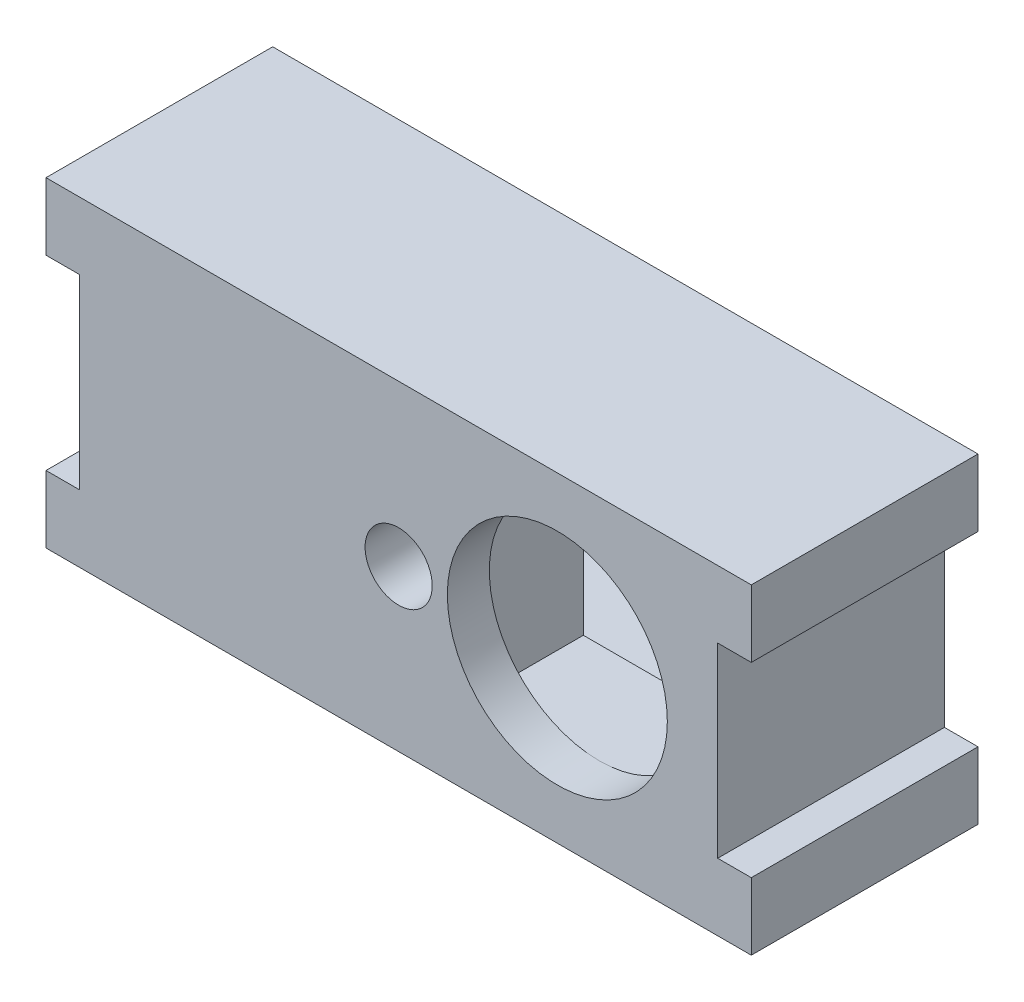
SolidWorks part; units mm, degrees
ref_plane "Front Plane" through (0, 0, 0) normal (0, 0, 1) x (1, 0, 0)
ref_plane "Top Plane" through (0, 0, 0) normal (0, 1, 0) x (1, 0, 0)
ref_plane "Right Plane" through (0, 0, 0) normal (1, 0, 0) x (0, 0, -1)
sketch "Sketch2" plane through (0, 0, 0) normal (0, 0, 1) x (1, 0, 0)
  line L0 (-19, 9.55) -> (-19, -9.55)
  line L1 (-16, 6.55) -> (16, 6.55) construction
  line L2 (-16, 6.55) -> (-16, -6.55) construction
  line L3 (-16, -6.55) -> (16, -6.55) construction
  line L4 (16, 6.55) -> (16, -6.55) construction
  line L5 (-16, 6.55) -> (16, -6.55) construction
  line L6 (-16, -6.55) -> (16, 6.55) construction
  line L7 (-19, -9.55) -> (19, -9.55)
  line L8 (19, 9.55) -> (19, -9.55)
  line L9 (-19, 9.55) -> (19, 9.55)
  circle A0 centre (9.45, 0) radius 6.55
  circle A1 centre (0, 0) radius 2
  point P0 (0, 0)
  point P15 (-16, 0)
  dimension "D5" = 4
  dimension "D1" = 32
  dimension "D2" = 13.1
  dimension "D4" = 16
  dimension "D3" = 3
extrude "Boss-Extrude1" add sketch "Sketch2" against normal blind 2.5
sketch "Sketch3" plane through (0, 0, -2.5) normal (0, 0, -1) x (-1, 0, 0)
  line L0 (-2.5, 6.55) -> (-2.5, -6.55)
  line L1 (19, 9.55) -> (-19, 9.55) construction
  line L2 (19, -9.55) -> (-19, -9.55) construction
  line L3 (-19, -9.55) -> (19, -9.55)
  line L4 (19, -9.55) -> (19, -5.55)
  line L5 (19, -5.55) -> (2.5, -5.55)
  line L6 (2.5, -5.55) -> (2.5, 5.55)
  line L7 (2.5, 5.55) -> (19, 5.55)
  line L9 (19, 9.55) -> (-19, 9.55)
  line L10 (19, 9.55) -> (19, -9.55) construction
  line L11 (16, 6.55) -> (-16, 6.55) construction
  line L12 (-2.5, 6.55) -> (-16, 6.55)
  line L13 (-16, 6.55) -> (-16, -6.55) construction
  line L14 (-16, 6.55) -> (-16, -6.55)
  line L16 (19, 9.55) -> (19, 5.55)
  line L17 (-2.5, -6.55) -> (-16, -6.55)
  line L18 (-19, 9.55) -> (-19, -9.55)
  line L19 (16, -6.55) -> (-16, -6.55) construction
  circle A0 centre (0, 0) radius 2 construction
  circle A1 centre (0, 0) radius 2
  dimension "D1" = 1
  dimension "D2" = 1
  dimension "D3" = 2.5
  dimension "D4" = 5
extrude "Boss-Extrude2" add sketch "Sketch3" along normal blind 6
sketch "Sketch4" plane through (0, 0, -8.5) normal (0, 0, -1) x (-1, 0, 0)
  line L4 (19, 5.55) -> (16.5, 5.55)
  line L5 (-19, -9.55) -> (19, -9.55)
  line L6 (-19, -9.55) -> (-19, 9.55)
  line L7 (-19, 9.55) -> (19, 9.55)
  line L8 (16.5, -7.05) -> (16.5, 7.05)
  line L9 (-16.5, -7.05) -> (16.5, -7.05)
  line L10 (-16.5, 7.05) -> (-16.5, -7.05)
  line L11 (16.5, 7.05) -> (-16.5, 7.05)
  line L12 (16.5, -7.05) -> (16.5, -5.55)
  line L13 (-16.5, -7.05) -> (16.5, -7.05)
  line L14 (-16.5, 7.05) -> (-16.5, -7.05)
  line L15 (16.5, 7.05) -> (-16.5, 7.05)
  line L16 (19, -9.55) -> (19, -5.55)
  line L17 (19, -5.55) -> (16.5, -5.55)
  line L18 (16.5, 5.55) -> (16.5, 7.05)
  line L19 (19, 5.55) -> (19, 9.55)
  dimension "D1" = 0.5
extrude "Boss-Extrude3" add sketch "Sketch4" along normal blind 5
sketch "Sketch5" plane through (0, 0, -13.5) normal (0, 0, -1) x (-1, 0, 0)
  line L0 (-19, 9.55) -> (-21, 9.55)
  line L1 (-19, 9.55) -> (-19, -9.55) construction
  line L2 (-21, 9.55) -> (-21, 5.55)
  line L3 (-21, 5.55) -> (-19, 5.55)
  line L4 (-19, 5.55) -> (-19, 9.55)
  line L6 (7.425, 0) -> (-7.425, 0) construction
  line L7 (-19, -5.55) -> (-19, -9.55)
  line L8 (-21, -9.55) -> (-21, -5.55)
  line L9 (-21, -5.55) -> (-19, -5.55)
  line L10 (-19, -9.55) -> (-21, -9.55)
  line L12 (16.5, 5.55) -> (19, 5.55) construction
  line L13 (19, 9.55) -> (-19, 9.55) construction
  point P4 (-19, 9.55)
  point P7 (-19, 9.55)
  point P14 (-19, 8.55)
  point P15 (-19, 8.55)
  dimension "D4" = 2
extrude "Boss-Extrude4" add sketch "Sketch5" against normal up to surface (13.5 mm away) up to face at (2, 0, 0)
mirror "Mirror1" about plane through (0, 0, 0) normal (1, 0, 0) of "Boss-Extrude4"
